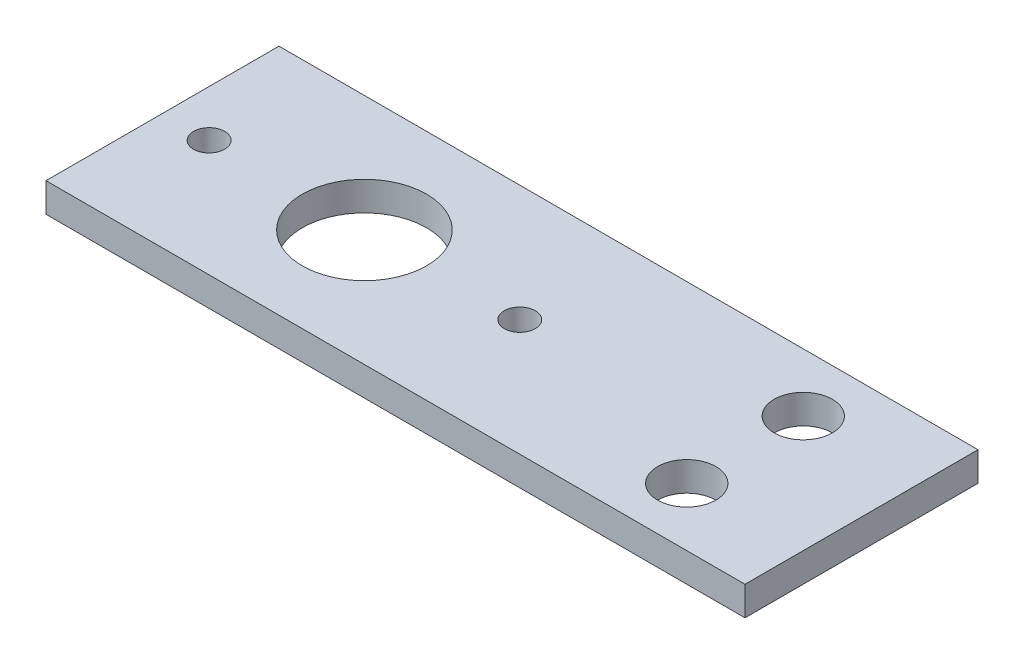
SolidWorks part; units mm, degrees
ref_plane "Front Plane" through (0, 0, 0) normal (0, 0, 1) x (1, 0, 0)
ref_plane "Top Plane" through (0, 0, 0) normal (0, 1, 0) x (1, 0, 0)
ref_plane "Right Plane" through (0, 0, 0) normal (1, 0, 0) x (0, 0, -1)
sketch "Sketch3" plane through (0, 0, 0) normal (0, 1, 0) x (1, 0, 0)
  line L0 (-114.3, 36.8038) -> (-114.3, -48.401) construction
  line L1 (-114.3, -19.05) -> (0, -19.05)
  line L2 (-114.3, -19.05) -> (-114.3, 19.05)
  line L3 (-114.3, 19.05) -> (0, 19.05)
  line L5 (0, 19.05) -> (0, -19.05) construction
  line L6 (-114.3, 0) -> (228.6, 0) construction
  line L7 (-114.3, 36.8038) -> (-48.26, 36.8038) construction
  line L8 (-48.26, 36.8038) -> (-48.26, -48.4673) construction
  line L9 (-81.28, 36.8038) -> (-81.28, -48.4673) construction
  line L10 (0, 19.05) -> (0, -19.05)
  line L11 (-37.0949, 0) -> (-37.0949, 19.05) construction
  circle A0 centre (-106.68, 0) radius 2.54
  circle A1 centre (-81.28, 0) radius 10.16
  circle A2 centre (-55.88, 0) radius 2.54
  circle A4 centre (-19.05, 9.525) radius 4.7625
  circle A5 centre (-19.05, -9.525) radius 4.7625
  point P0 (0, 0)
  point P21 (-19.05, 9.525)
  dimension "D4" = 20.32
  dimension "D6" = 5.08
  dimension "D2" = 19.05
  dimension "D11" = 9.525
  dimension "D1" = 114.3
  dimension "D3" = 50.8
  dimension "D5" = 25.4
  dimension "D7" = 66.04
  dimension "D8" = 33.02
  dimension "D9" = 19.05
  dimension "D10" = 38.1
extrude "Boss-Extrude1" add sketch "Sketch3" along normal blind 4.7625
